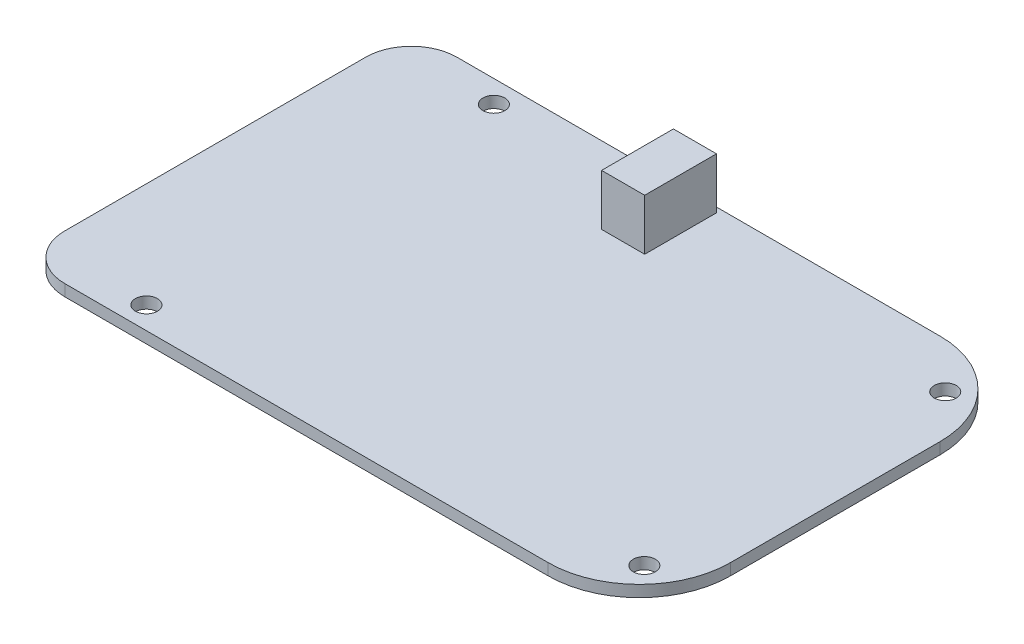
SolidWorks part; units mm, degrees
ref_plane "Front Plane" through (0, 0, 0) normal (0, 0, 1) x (1, 0, 0)
ref_plane "Top Plane" through (0, 0, 0) normal (0, 1, 0) x (1, 0, 0)
ref_plane "Right Plane" through (0, 0, 0) normal (1, 0, 0) x (0, 0, -1)
sketch "Sketch1" plane through (0, 0, 0) normal (0, 1, 0) x (1, 0, 0)
  line L0 (6.35, 54.61) -> (73.66, 54.61)
  line L1 (0, 48.26) -> (0, 6.35)
  line L2 (6.35, 0) -> (73.66, 0)
  line L3 (86.36, 12.7) -> (86.36, 41.91)
  line L4 (0, 6.35) -> (0, 0) construction
  line L5 (6.35, 0) -> (0, 0) construction
  arc A0 (6.35, 54.61) -> (0, 48.26) centre (6.35, 48.26) ccw
  arc A1 (0, 6.35) -> (6.35, 0) centre (6.35, 6.35) ccw
  arc A2 (73.66, 54.61) -> (86.36, 41.91) centre (73.66, 41.91) cw
  arc A3 (73.66, 0) -> (86.36, 12.7) centre (73.66, 12.7) ccw
  point P8 (40.005, 0)
  point P12 (40.005, 54.61)
  point P14 (0, 27.305)
  point P15 (86.36, 27.305)
  dimension "D2" = 6.35
  dimension "D4" = 12.7
  dimension "D1" = 12.7
  dimension "D3" = 6.35
  dimension "D5" = 54.61
  dimension "D6" = 86.36
extrude "Boss-Extrude1" add sketch "Sketch1" along normal blind 1.6
sketch "Sketch3" plane through (0, 1.6, 0) normal (0, 1, 0) x (1, 0, 0)
  line L0 (0, 48.26) -> (0, 6.35) construction
  line L1 (86.36, 12.7) -> (86.36, 41.91) construction
  line L3 (14.61, 3.11) -> (14.61, 0) construction
  line L4 (6.35, 0) -> (73.66, 0) construction
  line L5 (14.61, 3.11) -> (14.61, 51.5) construction
  line L6 (80.71, 6.35) -> (80.71, 48.26) construction
  line L7 (14.61, 27.305) -> (80.71, 27.305) construction
  circle A1 centre (80.71, 6.35) radius 1.53
  circle A3 centre (14.61, 3.11) radius 1.53
  circle A4 centre (14.61, 51.5) radius 1.53
  circle A5 centre (80.71, 48.26) radius 1.53
  point P21 (86.36, 27.305)
  point P22 (80.71, 27.305)
  dimension "D8" = 3.06
  dimension "D2" = 66.1
  dimension "D4" = 14.61
  dimension "D5" = 5.65
  dimension "D7" = 48.39
  dimension "D9" = 41.91
extrude "Cut-Extrude1" cut sketch "Sketch3" against normal blind 1.6
sketch "Sketch4" plane through (0, 1.6, 0) normal (0, 1, 0) x (1, 0, 0)
  line L0 (43.2, 43.91) -> (0, 43.91) construction
  line L4 (37.2, 43.91) -> (43.2, 43.91)
  line L5 (43.2, 43.91) -> (43.2, 53.91)
  line L6 (43.2, 53.91) -> (37.2, 53.91)
  line L7 (37.2, 53.91) -> (37.2, 43.91)
  line L8 (0, 48.26) -> (0, 6.35) construction
  line L9 (43.2, 43.91) -> (43.2, 54.61) construction
  line L10 (73.66, 54.61) -> (6.35, 54.61) construction
  dimension "D1" = 6
  dimension "D2" = 10
  dimension "D3" = 43.2
  dimension "D4" = 10.7
extrude "Boss-Extrude2" add sketch "Sketch4" along normal blind 7.12
sketch "Sketch5" plane through (0, 0, 0) normal (0, -1, 0) x (1, 0, 0)
  line L0 (15.3, 0) -> (15.3, -32) construction
  line L1 (6.35, 0) -> (73.66, 0) construction
  line L2 (15.3, -32) -> (0, -32)
  line L3 (0, -48.26) -> (0, -6.35) construction
  line L4 (15.3, -32) -> (15.3, -18)
  line L5 (15.3, -18) -> (0, -18)
  line L6 (0, -18) -> (0, -32)
  dimension "D1" = 15.3
  dimension "D2" = 32
  dimension "D3" = 14
extrude "Boss-Extrude3" add sketch "Sketch5" along normal blind 1.7
sketch "Sketch6" plane through (0, 0, 0) normal (0, -1, 0) x (-1, 0, 0)
  line L0 (0, 43.61) -> (-25.3, 43.61) construction
  line L1 (0, 48.26) -> (0, 32) construction
  line L2 (-25.3, 50.61) -> (-25.3, 54.61) construction
  line L4 (-25.3, 43.61) -> (-25.3, 50.61)
  line L5 (-25.3, 50.61) -> (-19.3, 50.61)
  line L6 (-19.3, 50.61) -> (-19.3, 43.61)
  line L7 (-19.3, 43.61) -> (-25.3, 43.61)
  line L8 (-73.66, 54.61) -> (-6.35, 54.61) construction
  dimension "D1" = 25.3
  dimension "D2" = 7
  dimension "D3" = 6
  dimension "D4" = 4
extrude "Boss-Extrude4" add sketch "Sketch6" along normal blind 4.6
sketch "Sketch7" plane through (0, 0, 0) normal (0, -1, 0) x (1, 0, 0)
  line L0 (0, -46.01) -> (50.3, -46.01) construction
  line L1 (0, -48.26) -> (0, -32) construction
  line L2 (50.3, -46.01) -> (50.3, -54.61) construction
  line L3 (73.66, -54.61) -> (6.35, -54.61) construction
  line L4 (50.3, -46.01) -> (44, -46.01)
  line L5 (44, -46.01) -> (44, -52.76)
  line L6 (44, -52.76) -> (50.3, -52.76)
  line L7 (50.3, -52.76) -> (50.3, -46.01)
  dimension "D1" = 50.3
  dimension "D2" = 8.6
  dimension "D3" = 6.75
  dimension "D4" = 6.3
extrude "Boss-Extrude5" add sketch "Sketch7" along normal blind 4.6
sketch "Sketch8" plane through (0, 0, 0) normal (0, -1, 0) x (1, 0, 0)
  line L0 (86.36, -44.41) -> (57.36, -44.41) construction
  line L1 (86.36, -12.7) -> (86.36, -41.91) construction
  line L2 (57.36, -44.41) -> (57.36, -54.61) construction
  line L3 (73.66, -54.61) -> (6.35, -54.61) construction
  line L4 (65.86, -44.41) -> (57.36, -44.41)
  line L5 (57.36, -44.41) -> (57.36, -52.91)
  line L6 (57.36, -52.91) -> (65.86, -52.91)
  line L7 (65.86, -52.91) -> (65.86, -44.41)
  dimension "D1" = 29
  dimension "D2" = 10.2
  dimension "D3" = 8.5
  dimension "D4" = 8.5
extrude "Boss-Extrude6" add sketch "Sketch8" along normal blind 4.6
